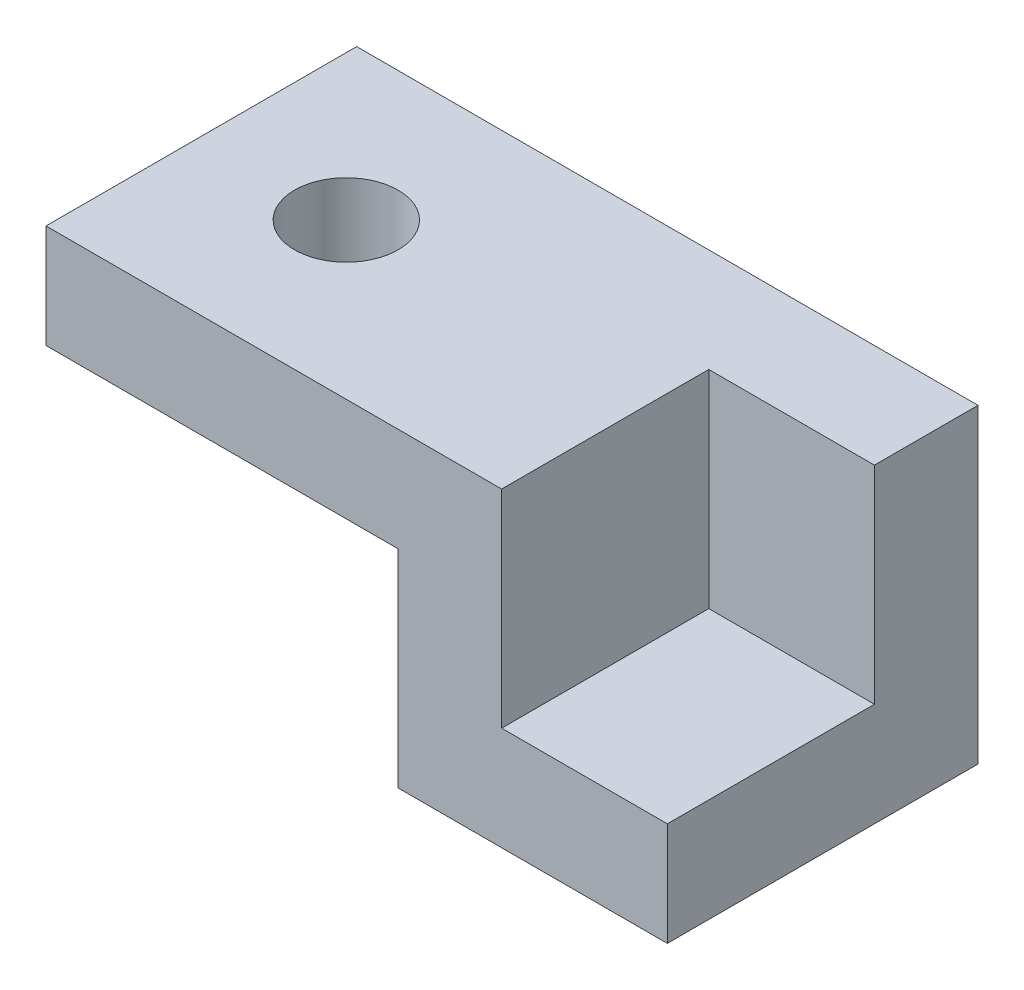
SolidWorks part; units mm, degrees
ref_plane "Front Plane" through (0, 0, 0) normal (0, 0, 1) x (1, 0, 0)
ref_plane "Top Plane" through (0, 0, 0) normal (0, 1, 0) x (1, 0, 0)
ref_plane "Right Plane" through (0, 0, 0) normal (1, 0, 0) x (0, 0, -1)
sketch "Sketch2" plane through (0, 0, 0) normal (0, 0, 1) x (1, 0, 0)
  line L1 (0, 0) -> (-65, 0)
  line L2 (0, 0) -> (0, 75)
  line L3 (0, 75) -> (-150, 75)
  line L4 (-65, 0) -> (-65, 50)
  line L7 (-65, 50) -> (-150, 50)
  line L8 (-150, 75) -> (-150, 50)
  point P8 (0, 0)
  dimension "D1" = 65
  dimension "D2" = 75
  dimension "D3" = 150
  dimension "D4" = 25
extrude "Boss-Extrude1" add sketch "Sketch2" along normal blind 75
sketch "Sketch4" plane through (0, 0, 75) normal (0, 0, 1) x (1, 0, 0)
  line L1 (0, 75) -> (-40, 75)
  line L2 (0, 75) -> (0, 25)
  line L3 (0, 25) -> (-40, 25)
  line L4 (-40, 75) -> (-40, 25)
  dimension "D1" = 50
  dimension "D2" = 40
extrude "Cut-Extrude1" cut sketch "Sketch4" against normal blind 50
sketch "Sketch5" plane through (0, 75, 0) normal (0, 1, 0) x (1, 0, 0)
  line L0 (-150, 0) -> (-150, -75) construction
  circle A0 centre (-115, -37.5) radius 12.5
  point P6 (0, 0)
  point P7 (-150, -37.5)
  dimension "D1" = 35
  dimension "D2" = 25
extrude "Cut-Extrude2" cut sketch "Sketch5" against normal up to surface (25 mm away) up to face at (-107.5, 50, 37.5)
